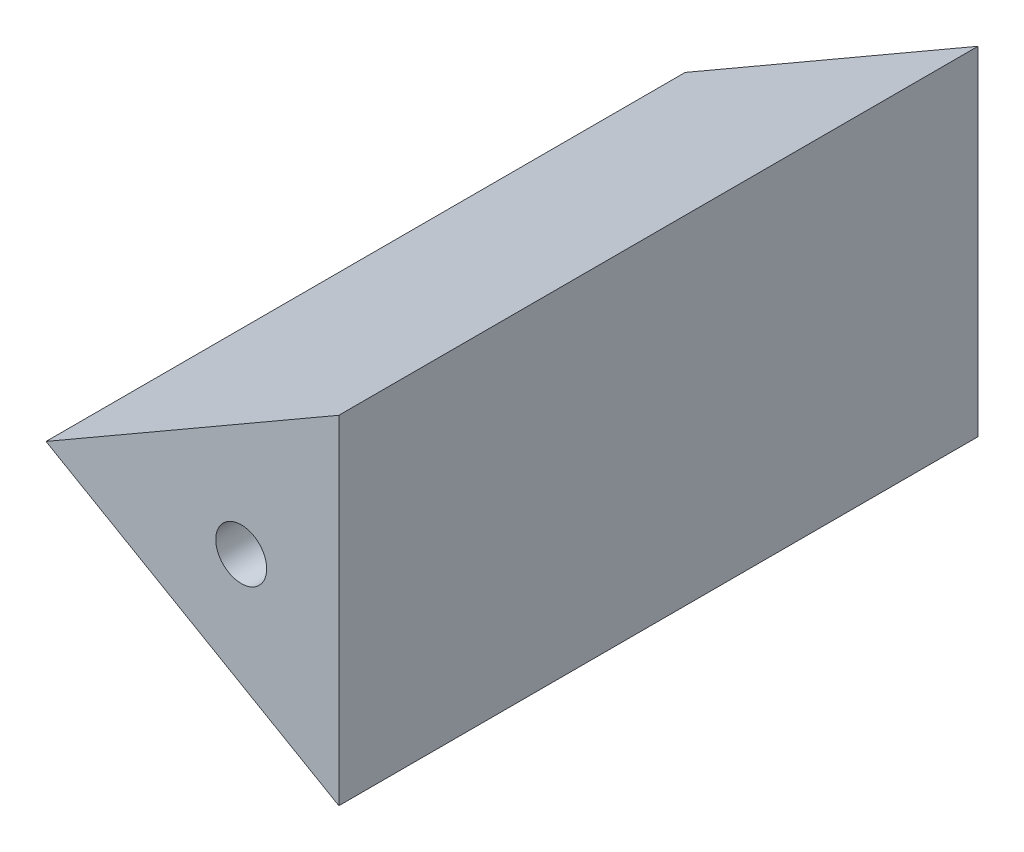
SolidWorks part; units mm, degrees
ref_plane "Front Plane" through (0, 0, 0) normal (0, 0, 1) x (1, 0, 0)
ref_plane "Top Plane" through (0, 0, 0) normal (0, 1, 0) x (1, 0, 0)
ref_plane "Right Plane" through (0, 0, 0) normal (1, 0, 0) x (0, 0, -1)
sketch "Sketch2" plane through (0, 0, 0) normal (0, 0, 1) x (1, 0, 0)
  line L1 (15.2729, 26.4535) -> (-30.5458, 0)
  line L2 (-30.5458, 0) -> (15.2729, -26.4535)
  line L3 (15.2729, -26.4535) -> (15.2729, 26.4535)
  circle A0 centre (0, 0) radius 15.2729 construction
extrude "Boss-Extrude2" add sketch "Sketch2" along normal blind 100 contours L1 L2 L3
sketch "Sketch3" plane through (0, 0, 100) normal (0, 0, 1) x (1, 0, 0)
  circle A0 centre (0, 0) radius 3.9821
extrude "Cut-Extrude1" cut sketch "Sketch3" against normal blind 100
